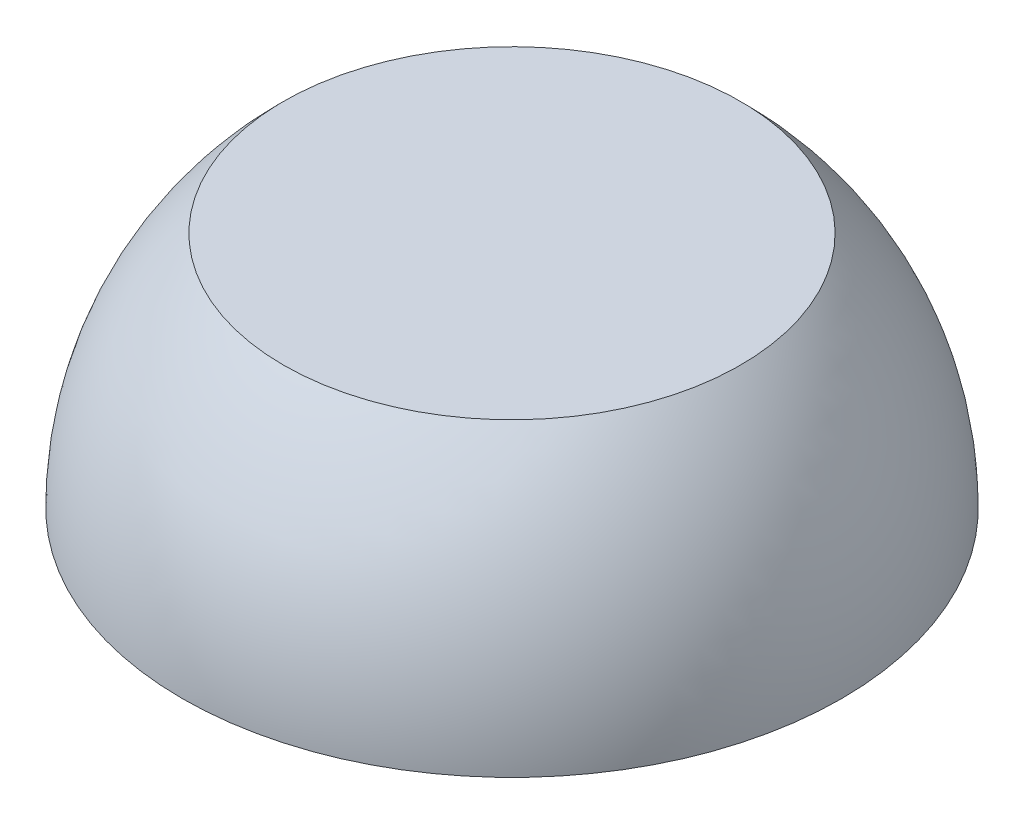
SolidWorks part; units mm, degrees
ref_plane "Front Plane" through (0, 0, 0) normal (0, 0, 1) x (1, 0, 0)
ref_plane "Top Plane" through (0, 0, 0) normal (0, 1, 0) x (1, 0, 0)
ref_plane "Right Plane" through (0, 0, 0) normal (1, 0, 0) x (0, 0, -1)
sketch "Sketch1" plane through (0, 0, 0) normal (0, 0, 1) x (1, 0, 0)
  line L0 (0, 0) -> (0, -11.3847) construction
  line L1 (2.0097, -5.3326) -> (0, -5.3326)
  line L2 (2.9, -7.4275) -> (0, -7.4275)
  line L3 (0, -5.3326) -> (0, -7.4275)
  arc A0 (2.9, -7.4275) -> (2.0097, -5.3326) centre (-0.01, -7.4275) ccw
  dimension "D2" = 2.91
  dimension "D1" = 2.9
revolve "Revolve1" add sketch "Sketch1" angle 360 about L0
